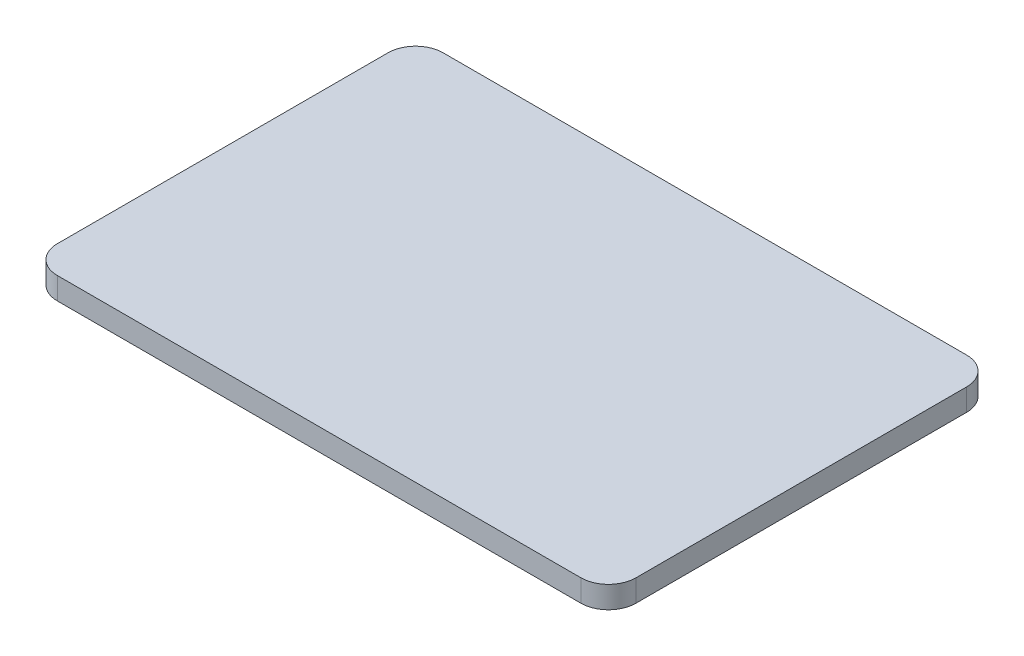
SolidWorks part; units mm, degrees
ref_plane "Front Plane" through (0, 0, 0) normal (0, 0, 1) x (1, 0, 0)
ref_plane "Top Plane" through (0, 0, 0) normal (0, 1, 0) x (1, 0, 0)
ref_plane "Right Plane" through (0, 0, 0) normal (1, 0, 0) x (0, 0, -1)
sketch "Sketch1" plane through (0, 0, 0) normal (0, 1, 0) x (1, 0, 0)
  line L1 (0, 0) -> (42, 0)
  line L2 (0, 0) -> (0, 28)
  line L3 (0, 28) -> (42, 28)
  line L4 (42, 0) -> (42, 28)
  dimension "D1" = 42
  dimension "D2" = 28
extrude "Boss-Extrude1" add sketch "Sketch1" along normal blind 1.6
fillet "Fillet1" radius 2 4 edges at (0, 0.8, 0) (0, 0.8, -28) (42, 0.8, -28) (42, 0.8, 0)
